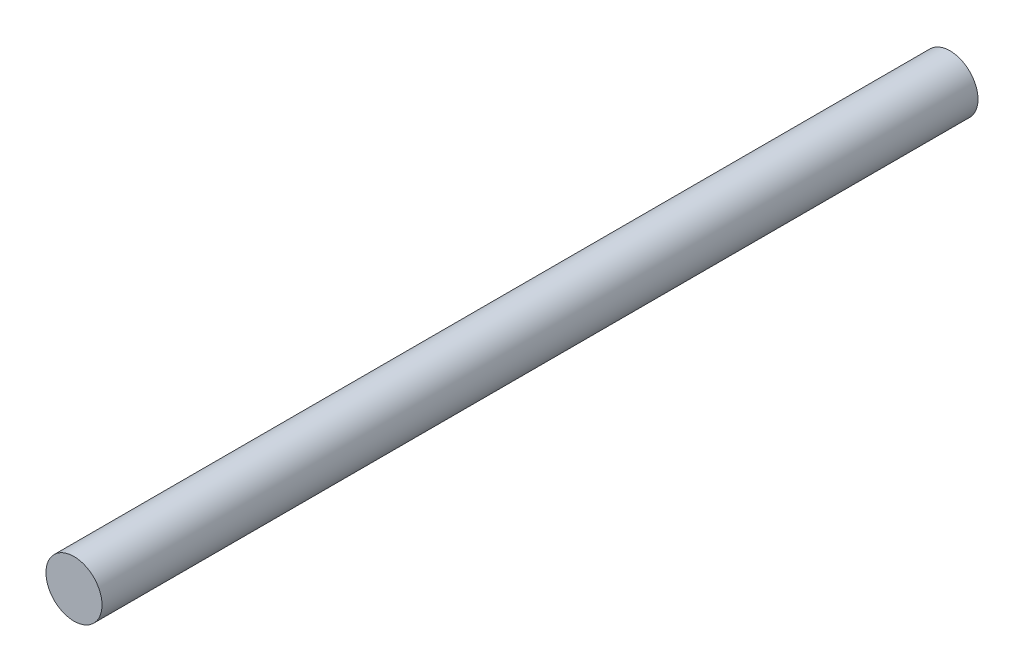
SolidWorks part; units mm, degrees
ref_plane "Piano frontale" through (0, 0, 0) normal (1, 0, 0) x (0, 1, 0)
ref_plane "Piano superiore" through (0, 0, 0) normal (0, 0, 1) x (0, 1, 0)
ref_plane "Piano destro" through (0, 0, 0) normal (0, 1, 0) x (-1, 0, 0)
sketch "Schizzo1" plane through (0, 0, 0) normal (0, 0, 1) x (0, 1, 0)
  circle A0 centre (0, 0) radius 1.6
  dimension "D1" = 3.2
extrude "Estrusione-Estrusione1" add sketch "Schizzo1" along normal blind 50
